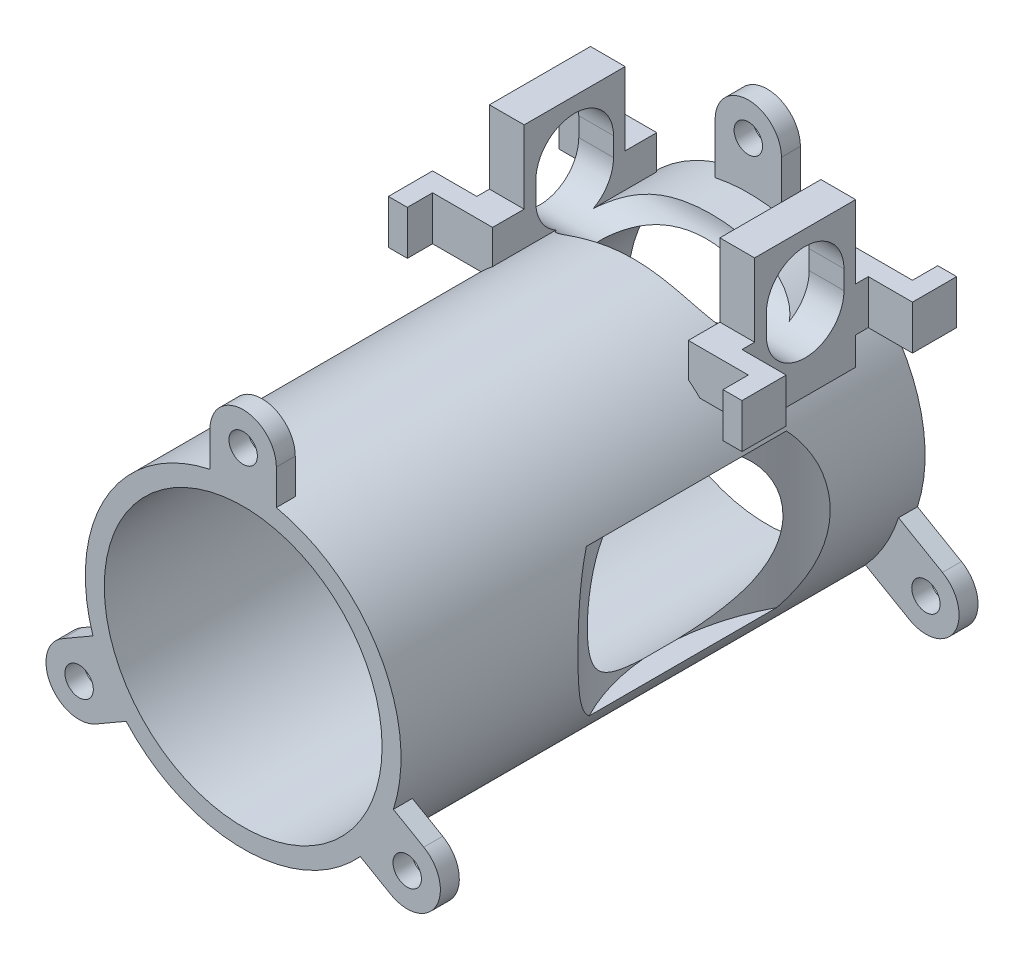
SolidWorks part; units mm, degrees
ref_plane "Front Plane" through (0, 0, 0) normal (0, 0, 1) x (1, 0, 0)
ref_plane "Top Plane" through (0, 0, 0) normal (0, 1, 0) x (1, 0, 0)
ref_plane "Right Plane" through (0, 0, 0) normal (1, 0, 0) x (0, 0, -1)
sketch "Sketch1" plane through (0, 0, 0) normal (0, 0, 1) x (1, 0, 0)
  circle A0 centre (0, 0) radius 22
  circle A1 centre (0, 0) radius 25
  dimension "D1" = 44
  dimension "D2" = 3
extrude "Boss-Extrude1" add sketch "Sketch1" along normal blind 30
ref_plane "Plane1" through (0, 0, 15) normal (0, 0, 1) x (1, 0, 0)
sketch "Sketch3" plane through (0, 0, 0) normal (1, 0, 0) x (0, 0, -1)
  line L0 (0, 25) -> (-30, 25) construction
  circle A0 centre (-15, 25) radius 6.15
  dimension "D1" = 12.3
extrude "Cut-Extrude1" cut sketch "Sketch3" against normal mid plane 50
sketch "Sketch7" plane through (0, 0, 30) normal (0, 0, 1) x (1, 0, 0)
  circle A0 centre (0, 0) radius 22
  circle A1 centre (0, 0) radius 25
extrude "Boss-Extrude4" add sketch "Sketch7" along normal blind 53
ref_plane "Plane2" through (-25, 0, 0) normal (-1, 0, 0) x (0, 0, 1)
sketch "Sketch9" plane through (0, 0, 0) normal (0, 0, -1) x (-1, 0, 0)
  line L0 (0, 0) -> (0, 32.4847) construction
  line L1 (-5.25, 32.4847) -> (-5.25, 24.4425)
  line L2 (5.25, 32.4847) -> (5.25, 24.4425)
  circle A0 centre (0, 32.4847) radius 2.25
  circle A1 centre (0, 32.4847) radius 5.25
  circle A2 centre (0, 0) radius 25 construction
  arc A3 (-5.25, 24.4425) -> (5.25, 24.4425) centre (0, 0) cw
  dimension "D1" = 4.5
  dimension "D2" = 3
extrude "Boss-Extrude5" add sketch "Sketch9" against normal blind 3
pattern_circular "CirPattern1" count 3 over 360 about axis through (0, 0, 0) along (0, 0, 1) of "Boss-Extrude5"
sketch "Sketch10" plane through (0, 0, 83) normal (0, 0, 1) x (1, 0, 0)
  line L0 (-5.25, 30) -> (-5.25, 24.4425)
  line L1 (5.25, 30) -> (5.25, 24.4425)
  line L2 (0, 0) -> (0, 30) construction
  circle A0 centre (0, 30) radius 2.25
  circle A1 centre (0, 30) radius 5.25
  arc A2 (-5.25, 24.4425) -> (5.25, 24.4425) centre (0, 0) cw
  circle A3 centre (0, 0) radius 25 construction
  circle M5 centre (0, 0) radius 25
  dimension "D2" = 4.5
  dimension "D3" = 30
  dimension "D1" = 3
extrude "Boss-Extrude6" add sketch "Sketch10" against normal blind 3 contours A1 A0 M5 | A1 L0 M5 | A1 L1 M5
pattern_circular "CirPattern2" count 3 every 120 about axis through (0, 0, 0) along (0, 0, 1) of "Boss-Extrude6"
ref_plane "Plane3" through (0, 11.51, 0) normal (0, 1, 0) x (1, 0, 0)
sketch "Sketch14" plane through (0, 0, 15) normal (0, 0, 1) x (1, 0, 0)
  line L0 (-21, 13.5647) -> (-21, 36.5647)
  line L1 (-21, 36.5647) -> (-15.5, 36.5647)
  line L2 (-15.5, 36.5647) -> (-15.5, 19.615)
  line L3 (-25, 27.5) -> (-25, -27.5) construction
  arc A0 (-5.25, 24.4425) -> (-23.7929, -7.6746) centre (0, 0) ccw construction
  arc A1 (-15.5, 19.615) -> (-21, 13.5647) centre (0, 0) ccw
  dimension "D1" = 23
  dimension "D2" = 4
  dimension "D3" = 5.5
extrude "Boss-Extrude7" add sketch "Sketch14" along normal mid plane 16
sketch "Sketch15" plane through (-21, 0, 0) normal (-1, 0, 0) x (0, 0, 1)
  line L0 (15, 25) -> (15, 28) construction
  line L1 (15, -27.5) -> (15, 27.5) construction
  line L2 (8.85, 25) -> (8.85, 28)
  line L3 (21.15, 25) -> (21.15, 28)
  line L4 (80, 25) -> (21.15, 25) construction
  arc A0 (8.85, 25) -> (21.15, 25) centre (15, 25) ccw
  arc A1 (21.15, 28) -> (8.85, 28) centre (15, 28) ccw
  point P4 (15, 26.5)
  dimension "D1" = 6.15
  dimension "D2" = 3
extrude "Cut-Extrude5" cut sketch "Sketch15" against normal blind 16
ref_plane "Plane5" through (0, 25, 0) normal (0, 1, 0) x (1, 0, 0)
sketch "Sketch17" plane through (0, 25, 0) normal (0, 1, 0) x (1, 0, 0)
  line L1 (-15.5, -23) -> (-21, -23)
  line L2 (-15.5, -23) -> (-15.5, -25)
  line L3 (-15.5, -25) -> (-21, -25)
  line L4 (-21, -23) -> (-21, -25)
  line L5 (-15.5, -23) -> (-21, -25) construction
  line L6 (-15.5, -25) -> (-21, -23) construction
  line L7 (-15.5, -25) -> (-28, -25)
  line L8 (-15.5, -25) -> (-15.5, -28)
  line L9 (-15.5, -28) -> (-28, -28)
  line L10 (-28, -25) -> (-28, -28)
  line L11 (-15.5, -25) -> (-28, -28) construction
  line L12 (-15.5, -28) -> (-28, -25) construction
  line L13 (-28, -28) -> (-25, -28)
  line L14 (-28, -28) -> (-28, -32)
  line L15 (-28, -32) -> (-25, -32)
  line L16 (-25, -28) -> (-25, -32)
  line L17 (-28, -28) -> (-25, -32) construction
  line L18 (-28, -32) -> (-25, -28) construction
  point P4 (-18.25, -24)
  point P10 (-21.75, -26.5)
  point P14 (-26.5, -30)
  dimension "D1" = 2
  dimension "D2" = 3
  dimension "D3" = 4
  dimension "D4" = 4
extrude "Boss-Extrude8" add sketch "Sketch17" against normal blind 7 contours L16 L9 L14 L15 | L7 L10 L9 L8 L3 | L1 L4 L3 L2
mirror "Mirror1" about plane through (0, 0, 15) normal (0, 0, 1) of "Boss-Extrude8"
mirror "Mirror2" about plane through (0, 0, 0) normal (1, 0, 0) of "Mirror1", "Boss-Extrude8", "Cut-Extrude5", "Boss-Extrude7"
sketch "Sketch12" plane through (0, 11.51, 0) normal (0, 1, 0) x (1, 0, 0)
  line L0 (0, -44.5194) -> (0, -33.7673) construction
  line L1 (-25.5075, 0) -> (-33.3825, 0) construction
  circle A0 centre (-50, -35) radius 30
  circle A1 centre (50, -35) radius 30
  circle A2 centre (-50, -35) radius 32
  circle A3 centre (50, -35) radius 32
  dimension "D1" = 60
  dimension "D2" = 100
  dimension "D3" = 35
  dimension "D4" = 2
extrude "Cut-Extrude4" cut sketch "Sketch12" against normal blind 24 contours A2 A0 | A1 | A3 A1
